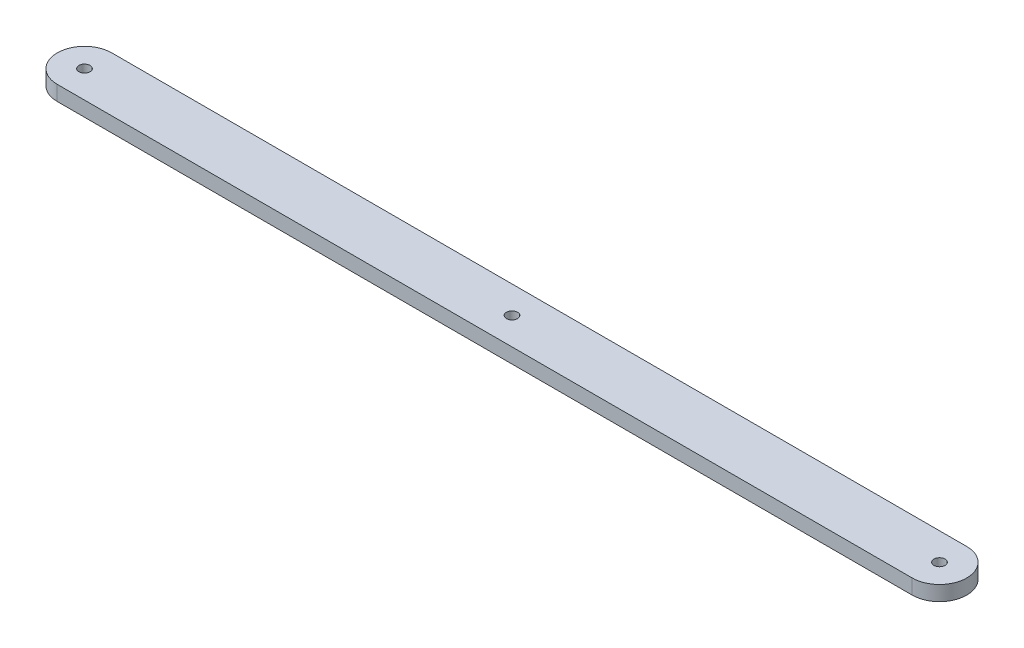
SolidWorks part; units mm, degrees
ref_plane "Front Plane" through (0, 0, 0) normal (0, 0, 1) x (1, 0, 0)
ref_plane "Top Plane" through (0, 0, 0) normal (0, 1, 0) x (1, 0, 0)
ref_plane "Right Plane" through (0, 0, 0) normal (1, 0, 0) x (0, 0, -1)
sketch "Sketch1" plane through (0, 0, 0) normal (0, 1, 0) x (1, 0, 0)
  line L0 (0, 0) -> (250, 0) construction
  line L1 (0, 7.9735) -> (250, 7.9735)
  line L2 (0, -7.9735) -> (250, -7.9735)
  arc A0 (0, 7.9735) -> (0, -7.9735) centre (0, 0) ccw
  arc A1 (250, -7.9735) -> (250, 7.9735) centre (250, 0) ccw
  circle A2 centre (250, 0) radius 1.625
  circle A3 centre (125, 0) radius 1.625
  circle A4 centre (0, 0) radius 1.625
  point P3 (125, 0)
  dimension "D1" = 3.25
  dimension "D2" = 3.25
  dimension "D3" = 3.25
extrude "Boss-Extrude1" add sketch "Sketch1" along normal blind 4.35
